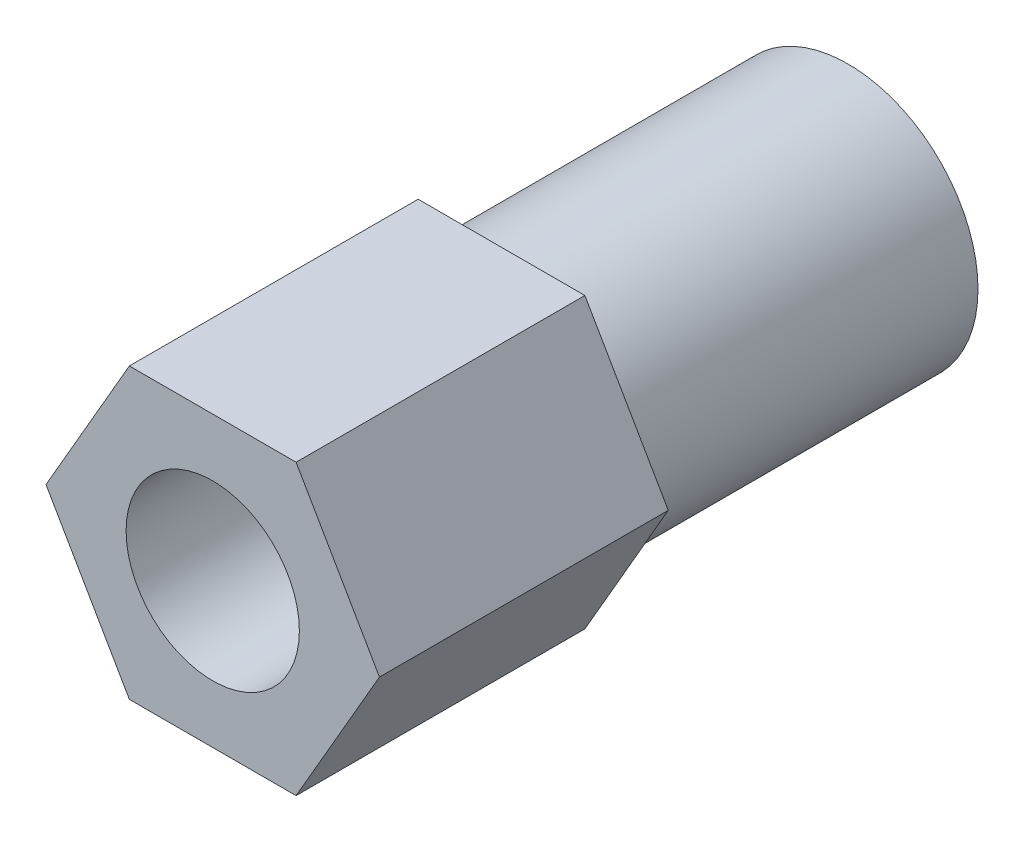
SolidWorks part; units mm, degrees
ref_plane "Plan de face" through (0, 0, 0) normal (0, 0, 1) x (1, 0, 0)
ref_plane "Plan de dessus" through (0, 0, 0) normal (0, 1, 0) x (1, 0, 0)
ref_plane "Plan de droite" through (0, 0, 0) normal (1, 0, 0) x (0, 0, -1)
sketch "Esquisse1" plane through (0, 0, 0) normal (0, 0, 1) x (1, 0, 0)
  line L1 (-2.8868, 0) -> (-1.4434, -2.5)
  line L2 (-1.4434, -2.5) -> (1.4434, -2.5)
  line L3 (1.4434, -2.5) -> (2.8868, 0)
  line L4 (2.8868, 0) -> (1.4434, 2.5)
  line L5 (1.4434, 2.5) -> (-1.4434, 2.5)
  line L6 (-1.4434, 2.5) -> (-2.8868, 0)
  circle A0 centre (0, 0) radius 1.5
  circle A1 centre (0, 0) radius 2.5 construction
  dimension "D1" = 3
  dimension "D2" = 5
extrude "Boss.-Extru.1" add sketch "Esquisse1" along normal blind 5
sketch "Esquisse2" plane through (0, 0, 0) normal (0, 0, -1) x (-1, 0, 0)
  circle A0 centre (0, 0) radius 2.25
  circle A1 centre (0, 0) radius 1.5
  dimension "D1" = 4.5
extrude "Boss.-Extru.2" add sketch "Esquisse2" along normal blind 6
